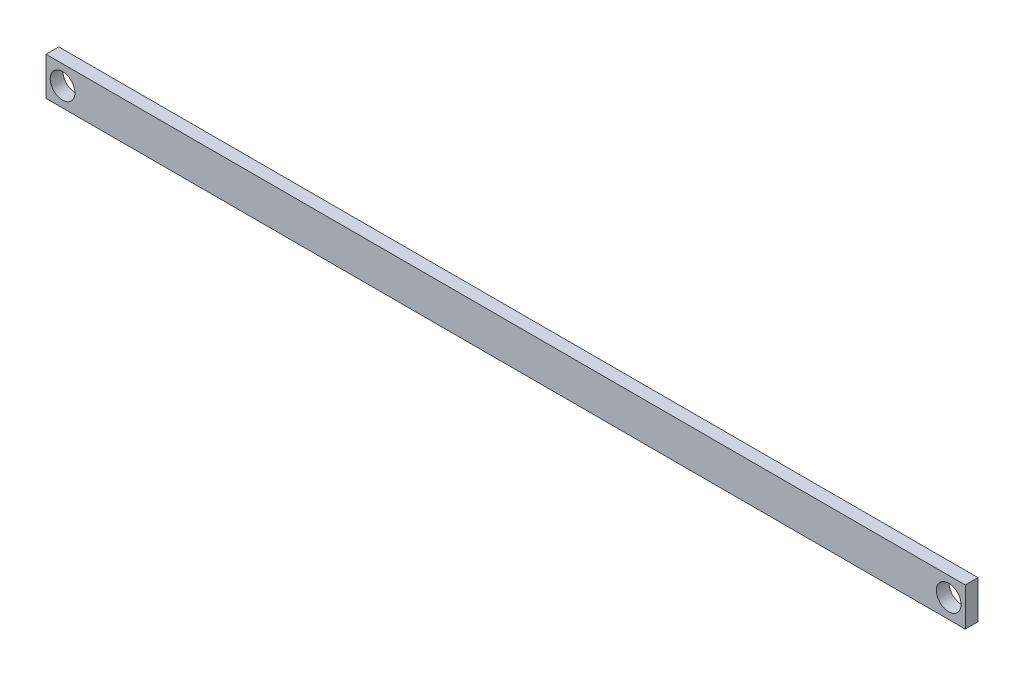
SolidWorks part; units mm, degrees
material "Plain Carbon Steel"
ref_plane "Front Plane" through (0, 0, 0) normal (0, 0, 1) x (1, 0, 0)
ref_plane "Top Plane" through (0, 0, 0) normal (0, 1, 0) x (1, 0, 0)
ref_plane "Right Plane" through (0, 0, 0) normal (1, 0, 0) x (0, 0, -1)
sketch "Sketch2" plane through (0, 0, 0) normal (0, 0, 1) x (1, 0, 0)
  line L0 (0, 0) -> (360.6, 0)
  line L1 (0, 0) -> (0, -15)
  line L2 (0, -15) -> (360.6, -15)
  line L3 (360.6, -15) -> (360.6, 0)
  dimension "D1" = 360.6
  dimension "D2" = 15
extrude "Boss-Extrude1" add sketch "Sketch2" against normal blind 5
sketch "Sketch3" plane through (0, 0, 0) normal (0, 0, 1) x (1, 0, 0)
  line L0 (0, 0) -> (0, -15) construction
  line L1 (360.6, -15) -> (360.6, 0) construction
  circle A0 centre (6.5, -7.5) radius 4.85
  circle A1 centre (354.1, -7.5) radius 4.85
  dimension "D1" = 9.7
  dimension "D3" = 9.7
  dimension "D2" = 6.5
  dimension "D4" = 6.5
extrude "Cut-Extrude1" cut sketch "Sketch3" against normal blind 5
